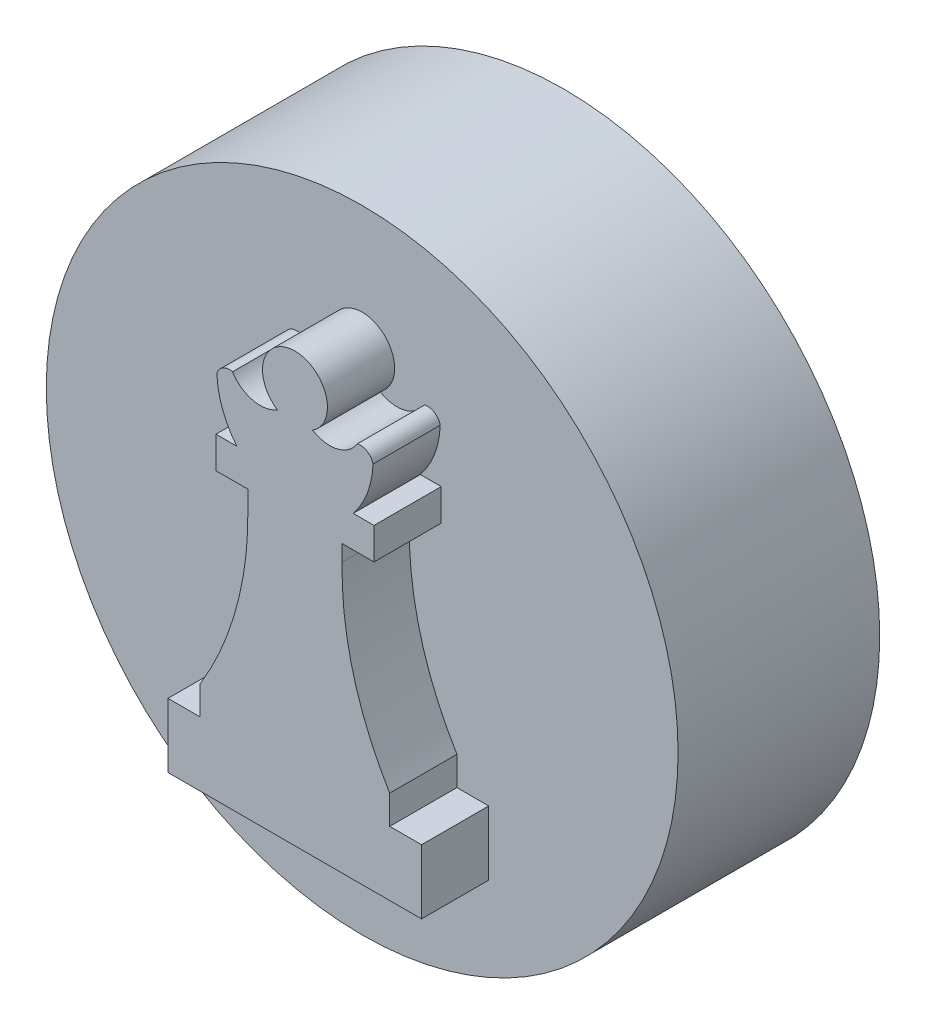
SolidWorks part; units mm, degrees
ref_plane "Front Plane" through (0, 0, 0) normal (0, 0, 1) x (1, 0, 0)
ref_plane "Top Plane" through (0, 0, 0) normal (0, 1, 0) x (1, 0, 0)
ref_plane "Right Plane" through (0, 0, 0) normal (1, 0, 0) x (0, 0, -1)
sketch "Sketch1" plane through (0, 0, 0) normal (0, 0, 1) x (1, 0, 0)
  circle A0 centre (0, 0) radius 8.763
  circle A1 centre (0, 0) radius 11.938
  dimension "D1" = 17.526
  dimension "D2" = 23.876
extrude "Boss-Extrude1" add sketch "Sketch1" along normal blind 5.08
sketch "Sketch2" plane through (0, 0, 5.08) normal (0, 0, 1) x (1, 0, 0)
  circle A0 centre (0, 0) radius 11.938
extrude "Boss-Extrude2" add sketch "Sketch2" along normal blind 2.54
sketch "Sketch3" plane through (0, 0, 7.62) normal (0, 0, 1) x (1, 0, 0)
  line L0 (76.4074, 247.7537) -> (417.7408, 247.7537) construction
  line L1 (0, 0) -> (0, 2.859) construction
  line L30 (33.3333, 100.0554) -> (166.6667, 100.0554) construction
  line L31 (76.5513, 248.4132) -> (417.8847, 248.4132) construction
  line L50 (33.4547, 119.6194) -> (204.1214, 119.6194) construction
  line L63 (146.8553, 495.6562) -> (829.522, 495.6562) construction
  line L64 (32.8546, 118.5983) -> (203.5213, 118.5983) construction
  line L88 (0, 4.0767) -> (0, 10.7108) construction
  line L102 (75.7654, 247.0659) -> (417.0987, 247.0659) construction
  line L103 (-3.5812, -5.3231) -> (-3.5812, -4.2346)
  line L104 (-4.7989, -7.7506) -> (4.7829, -7.7506)
  line L105 (-4.7989, -7.7506) -> (-4.7989, -5.3231)
  line L106 (-4.7989, -5.3231) -> (-3.5812, -5.3231)
  line L107 (4.7829, -7.7506) -> (4.7829, -5.3231)
  line L108 (-1.7803, 2.4233) -> (-1.7803, 3.033)
  line L109 (-2.2001, 4.2299) -> (-2.9866, 4.2299)
  line L110 (-2.9866, 4.2299) -> (-2.9866, 3.033)
  line L111 (-2.9866, 3.033) -> (-1.7803, 3.033)
  line L112 (2.2001, 4.2299) -> (2.9866, 4.2299)
  line L113 (2.9866, 4.2299) -> (2.9866, 3.033)
  line L114 (2.9866, 3.033) -> (1.7803, 3.033)
  line L115 (3.5812, -5.3231) -> (3.5812, -4.2346)
  line L116 (3.5812, -5.3231) -> (4.7829, -5.3231)
  line L117 (1.7803, 2.4233) -> (1.7803, 3.033)
  arc A25 (-3.5812, -4.2346) -> (-1.7803, 2.4233) centre (-14.1179, 2.1879) ccw
  arc A26 (0.6676, 6.1874) -> (-0.6676, 6.1874) centre (0, 7.2169) ccw
  arc A27 (-0.6676, 6.1874) -> (-2.3585, 6.5862) centre (-1.3136, 7.2322) cw
  arc A28 (-2.3585, 6.5862) -> (-2.9501, 6.2204) centre (-2.4714, 6.1075) ccw
  arc A29 (-2.2001, 4.2299) -> (-2.9501, 6.2204) centre (0.4152, 6.3519) cw
  arc A30 (2.3585, 6.5862) -> (2.9501, 6.2204) centre (2.4714, 6.1075) cw
  arc A31 (0.6676, 6.1874) -> (2.3585, 6.5862) centre (1.3136, 7.2322) ccw
  arc A32 (2.2001, 4.2299) -> (2.9501, 6.2204) centre (-0.4152, 6.3519) ccw
  arc A33 (3.5812, -4.2346) -> (1.7803, 2.4233) centre (14.1179, 2.1879) cw
extrude "Boss-Extrude7" add sketch "Sketch3" along normal blind 2.54 contours L117 L114 L113 L112 A32 A30 A31 A26 A27 A28 A29 L109 L110 L111 L108 A25 L103 L106 L105 L104 L107 L116 L115 A33
